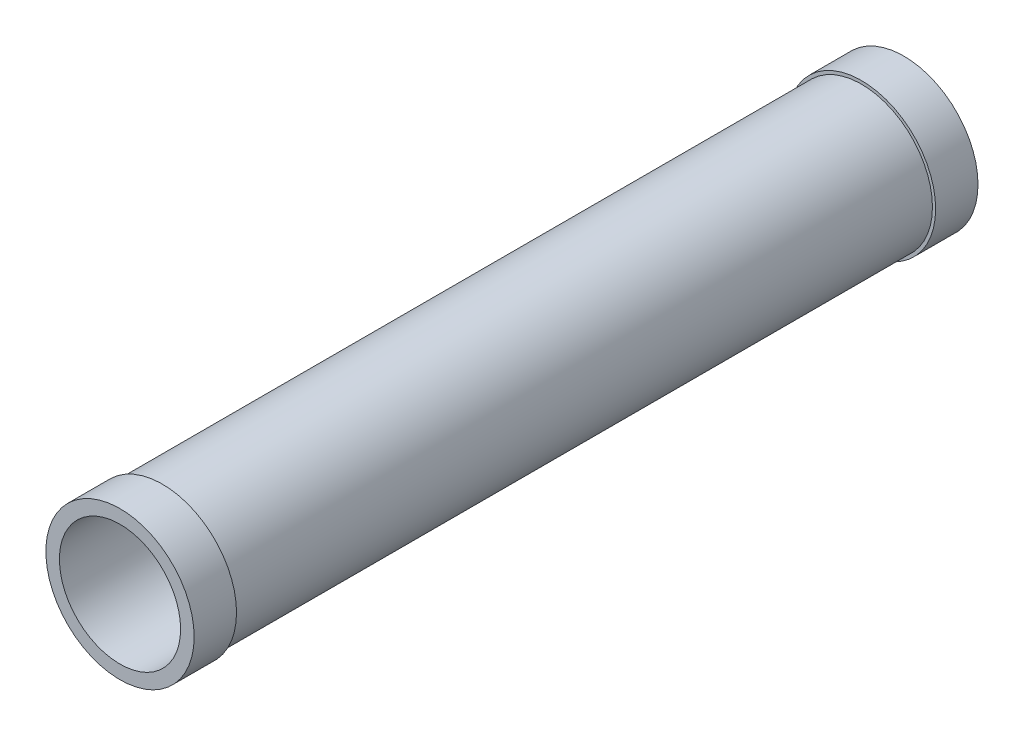
SolidWorks part; units mm, degrees
ref_plane "Plan de face" through (0, 0, 0) normal (0, 0, 1) x (1, 0, 0)
ref_plane "Plan de dessus" through (0, 0, 0) normal (0, 1, 0) x (1, 0, 0)
ref_plane "Plan de droite" through (0, 0, 0) normal (1, 0, 0) x (0, 0, -1)
sketch "Esquisse1" plane through (0, 0, 0) normal (0, 0, 1) x (1, 0, 0)
  circle A0 centre (0, 0) radius 14.3
  circle A1 centre (0, 0) radius 17.5
  dimension "D1" = 28.6
  dimension "D2" = 35
extrude "Boss.-Extru.1" add sketch "Esquisse1" along normal mid plane 185
sketch "Esquisse2" plane through (0, 0, 0) normal (0, 0, 1) x (1, 0, 0)
  circle A0 centre (0, 0) radius 16.75
  dimension "D1" = 33.5
extrude "Enlèv. mat.-Extru.1" cut sketch "Esquisse2" against normal mid plane 165 flip side to cut
